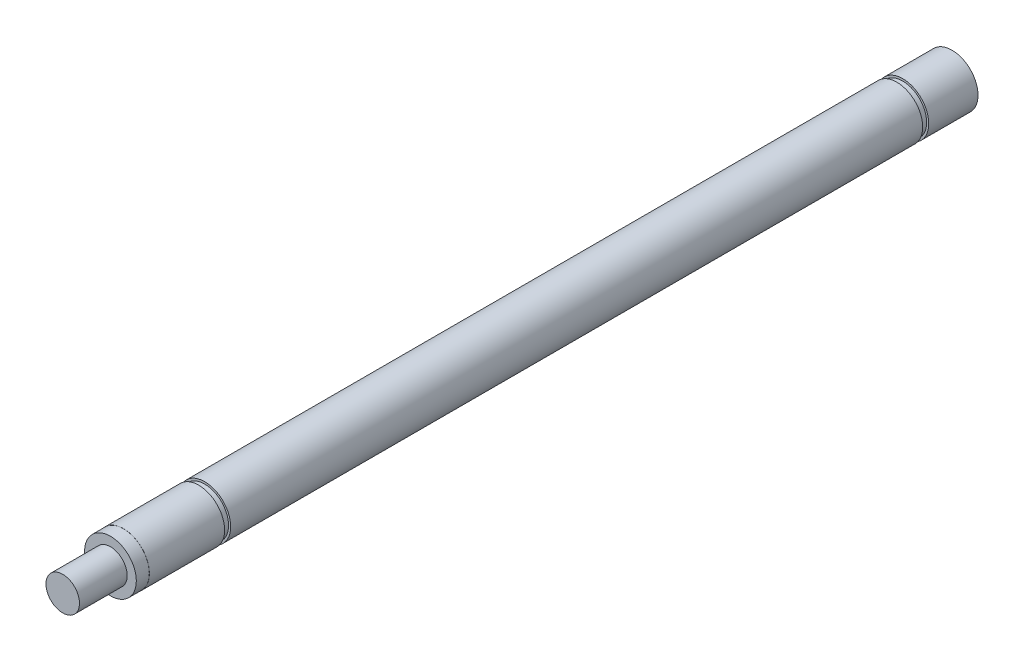
SolidWorks part; units mm, degrees
ref_plane "Front Plane" through (0, 0, 0) normal (0, 0, 1) x (1, 0, 0)
ref_plane "Top Plane" through (0, 0, 0) normal (0, 1, 0) x (1, 0, 0)
ref_plane "Right Plane" through (0, 0, 0) normal (1, 0, 0) x (0, 0, -1)
sketch "Sketch1" plane through (0, 0, 0) normal (0, 1, 0) x (1, 0, 0)
  line L0 (3.175, 99.7956) -> (-3.175, 99.7956) construction
  line L1 (4.915, -9.017) -> (-4.915, -9.017) construction
  line L2 (2.05, -1.5875) -> (2.05, -9.017) construction
  line L3 (4.915, -3.175) -> (-4.915, -3.175) construction
  line L4 (3.1623, -1.5875) -> (3.1623, -3.175) construction
  line L5 (3.175, -1.5875) -> (-3.175, -1.5875) construction
  line L6 (0, -1.5875) -> (0, 99.7956) construction
  line L7 (3.175, -1.5875) -> (3.175, 99.7956) construction
  line L8 (3.175, 99.7956) -> (0, 99.7956)
  line L9 (2.05, -9.017) -> (0, -9.017)
  line L10 (2.05, -3.175) -> (2.05, -9.017)
  line L11 (3.1623, -3.175) -> (2.05, -3.175)
  line L12 (3.1623, -1.5875) -> (3.1623, -3.175)
  line L13 (3.175, -1.5875) -> (3.1623, -1.5875)
  line L14 (0, -9.017) -> (0, 99.7956)
  line L15 (3.175, -1.5875) -> (3.175, 7.62)
  line L16 (3.175, 7.62) -> (2.921, 7.62) construction
  line L17 (2.921, 7.62) -> (2.921, 8.3566) construction
  line L18 (3.175, 8.3566) -> (2.921, 8.3566) construction
  line L19 (3.175, 93.0328) -> (2.921, 93.0328) construction
  line L20 (2.921, 93.7694) -> (2.921, 93.0328) construction
  line L21 (3.175, 93.7694) -> (2.921, 93.7694) construction
  line L22 (3.175, 7.62) -> (2.921, 7.62)
  line L23 (2.921, 7.62) -> (2.921, 8.3566)
  line L24 (3.175, 8.3566) -> (2.921, 8.3566)
  line L25 (3.175, 93.0328) -> (2.921, 93.0328)
  line L26 (2.921, 93.7694) -> (2.921, 93.0328)
  line L27 (3.175, 93.7694) -> (2.921, 93.7694)
  line L28 (3.175, 8.3566) -> (3.175, 93.0328)
  line L29 (3.175, 93.7694) -> (3.175, 99.7956)
revolve "Revolve1" add sketch "Sketch1" angle 360 about L14
